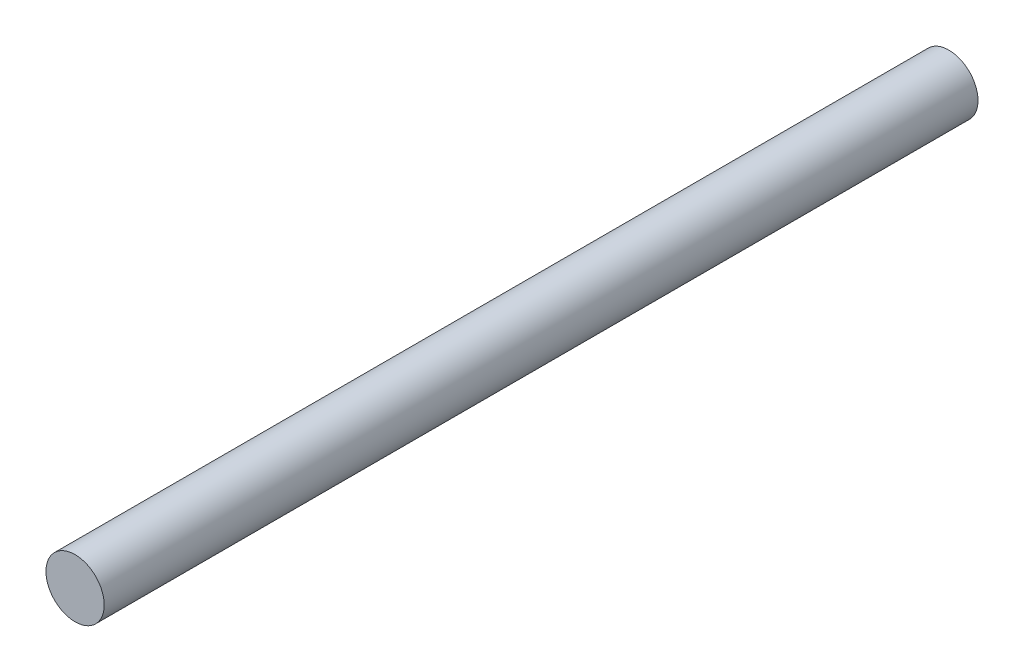
SolidWorks part; units mm, degrees
ref_plane "Plan de face" through (0, 0, 0) normal (0, 0, 1) x (1, 0, 0)
ref_plane "Plan de dessus" through (0, 0, 0) normal (0, 1, 0) x (1, 0, 0)
ref_plane "Plan de droite" through (0, 0, 0) normal (1, 0, 0) x (0, 0, -1)
sketch "Esquisse1" plane through (0, 0, 0) normal (0, 0, 1) x (1, 0, 0)
  circle A0 centre (0, 0) radius 4
  dimension "D1" = 8
extrude "Boss.-Extru.1" add sketch "Esquisse1" along normal blind 120
